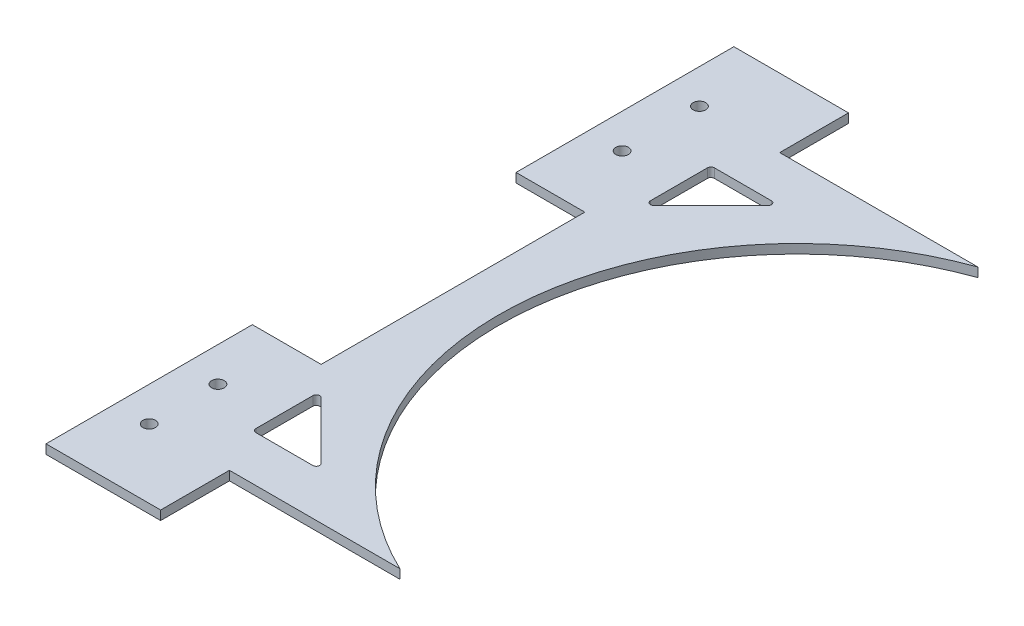
SolidWorks part; units mm, degrees
material "A-玻璃纤维"
ref_plane "前视基准面" through (0, 0, 0) normal (0, 0, 1) x (1, 0, 0)
ref_plane "上视基准面" through (0, 0, 0) normal (0, 1, 0) x (1, 0, 0)
ref_plane "右视基准面" through (0, 0, 0) normal (1, 0, 0) x (0, 0, -1)
other "Configuration Table"
sketch "草图1" plane through (0, 0, 0) normal (0, 1, 0) x (1, 0, 0)
  line L0 (0, 0) -> (360, 0)
  line L1 (360, 0) -> (360, -300)
  line L2 (360, -300) -> (0, -300)
  line L3 (0, -300) -> (0, 0)
  dimension "D1" = 360
  dimension "D2" = 300
extrude "凸台-拉伸1" add sketch "草图1" along normal blind 4
sketch "草图2" plane through (0, 4, 0) normal (0, 1, 0) x (1, 0, 0)
  line L0 (0, 0) -> (50, 0)
  line L1 (360, 0) -> (0, 0) construction
  line L2 (50, 0) -> (50, -30)
  line L3 (50, -30) -> (0, -30)
  line L4 (0, 0) -> (0, -300) construction
  line L5 (0, -30) -> (0, 0)
  line L6 (360, 0) -> (310, 0)
  line L7 (310, 0) -> (310, -30)
  line L8 (310, -30) -> (360, -30)
  line L9 (360, -300) -> (360, 0) construction
  line L10 (360, -30) -> (360, 0)
  line L11 (50, 0) -> (310, 0)
  line L12 (50, -30) -> (310, -30)
  line L13 (50, -30) -> (50, 0)
  line L14 (310, 0) -> (310, -30)
  line L15 (50, -30) -> (50, -300)
  line L16 (0, -300) -> (360, -300) construction
  line L17 (310, -30) -> (310, -297.4148)
  line L18 (310, -297.4148) -> (310, -308.1659)
  line L19 (0, -300) -> (0, -270)
  line L20 (0, -270) -> (360, -270)
  line M2 (0, -300) -> (360, -300)
  line M4 (360, 0) -> (0, 0)
extrude "切除-拉伸1" cut sketch "草图2" against normal through all contours L2 L12 L7 M4 | L20 L15 L18 L17 M2
sketch "草图3" plane through (0, 4, 0) normal (0, 1, 0) x (1, 0, 0)
  line L0 (0, -300) -> (30, -300)
  line L1 (0, -300) -> (50, -300) construction
  line L2 (30, -300) -> (30, -210)
  line L3 (30, -210) -> (0, -210)
  line L4 (0, 0) -> (0, -300) construction
  line L5 (0, 0) -> (0, -95)
  line L6 (0, -95) -> (30, -95)
  line L7 (30, -95) -> (30, -210)
  line L8 (0, -210) -> (0, -95)
  line L9 (360, -300) -> (310, -300)
  line L10 (310, -300) -> (310, -30)
  line L11 (30, -95) -> (360, -95)
  line L12 (360, -300) -> (360, 0) construction
  line L13 (30, -210) -> (360, -210)
  line L14 (360, -300) -> (330, -300)
  line L15 (330, -300) -> (330, 0)
  line L16 (360, 0) -> (310, 0) construction
  line M4 (0, 0) -> (0, -300)
  line M6 (360, -300) -> (360, 0)
extrude "切除-拉伸2" cut sketch "草图3" against normal through all contours L7 L6 L3 M4 | L15 L13 L11 M6
sketch "草图4" plane through (0, 4, 0) normal (0, 1, 0) x (1, 0, 0)
  line L0 (30, -152.5) -> (330, -152.5)
  line L1 (30, -95) -> (30, -210) construction
  line L2 (330, -210) -> (330, -95) construction
  line L3 (180, -30) -> (180, -270)
  line L4 (50, -30) -> (310, -30) construction
  line L5 (50, -270) -> (310, -270) construction
  circle A1 centre (180, -152.5) radius 130
  line M6 (50, -270) -> (310, -270)
  line M16 (310, -30) -> (50, -30)
extrude "切除-拉伸3" cut sketch "草图4" against normal through all contours A1 L0 L3 M16 | L0 A1 L3 M16 | L0 A1 L3 M6 | A1 L0 L3 M6
sketch "草图5" plane through (0, 4, 0) normal (0, 1, 0) x (1, 0, 0)
  line L0 (0, -300) -> (15, -300)
  line L1 (0, -300) -> (50, -300) construction
  line L2 (15, -300) -> (15, 0)
  line L3 (50, 0) -> (0, 0) construction
  line L4 (15, -300) -> (15, -270)
  line L5 (15, -270) -> (15, -240)
  line L6 (15, 0) -> (15, -30)
  line L7 (15, -30) -> (15, -63.744)
  circle A0 centre (15, -270) radius 2.75
  circle A1 centre (15, -240) radius 2.75
  circle A2 centre (15, -30) radius 2.75
  circle A3 centre (15, -63.744) radius 2.75
extrude "切除-拉伸4" cut sketch "草图5" against normal through all contours L7 A2 L2 | L2 A2 L7 | L2 A3 | L2 A3 | L2 A1 | L2 A1 | L4 A0 L2 | L2 A0 L4
sketch "草图6" plane through (0, 4, 0) normal (0, 1, 0) x (1, 0, 0)
  line L0 (50, -30) -> (50, -50)
  line L1 (50, -50) -> (66.3787, -50)
  line L2 (67.4393, -52.5607) -> (42.5607, -77.4393)
  line L3 (40, -76.3787) -> (40, -51.5)
  line L4 (41.5, -50) -> (50, -50)
  line L6 (41.5, -50) -> (41.5, -51.5)
  line L9 (41.4934, -76.3718) -> (41.5, -76.3787)
  arc A0 (41.5, -50) -> (40, -51.5) centre (41.5, -51.5) ccw
  arc A1 (40, -76.3787) -> (42.5607, -77.4393) centre (41.5, -76.3787) ccw
  arc A2 (67.4393, -52.5607) -> (66.3787, -50) centre (66.3787, -51.5) ccw
extrude "切除-拉伸5" cut sketch "草图6" against normal through all
ref_plane "基准面1" through (0, 0, 150) normal (0, 0, 1) x (1, 0, 0)
mirror "镜向1" about plane through (0, 0, 150) normal (0, 0, 1) of "切除-拉伸5"
